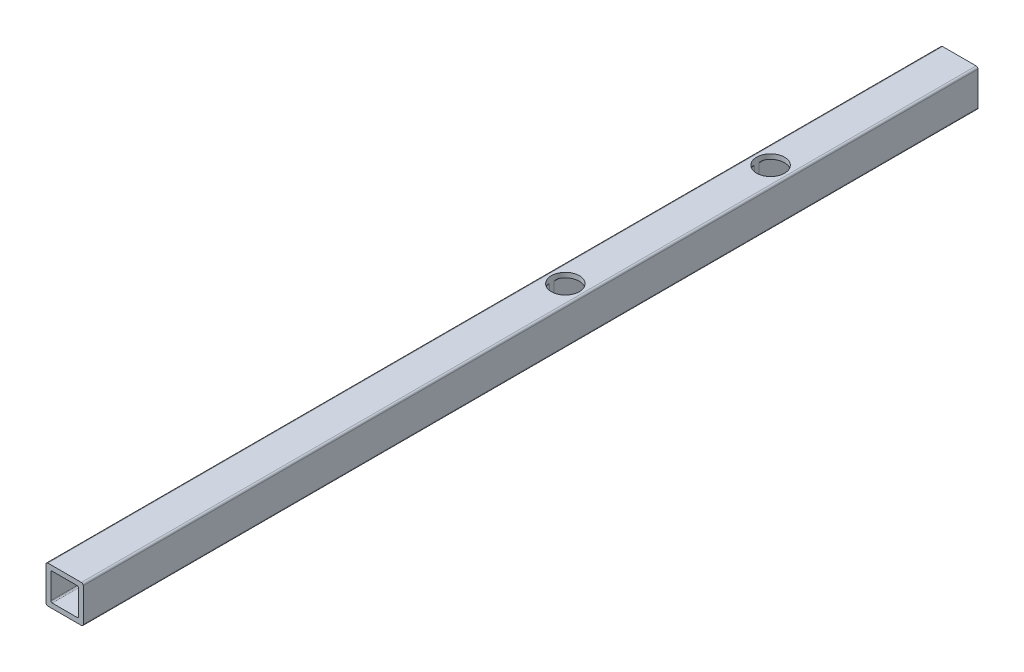
SolidWorks part; units mm, degrees
ref_plane "Front" through (0, 0, 0) normal (0, 0, 1) x (1, 0, 0)
ref_plane "Top" through (0, 0, 0) normal (0, 1, 0) x (1, 0, 0)
ref_plane "Right" through (0, 0, 0) normal (1, 0, 0) x (0, 0, -1)
sketch "Sketch1" plane through (0, 0, 0) normal (0, 0, 1) x (1, 0, 0)
  line L0 (-4.699, 0) -> (-6.35, 0) construction
  line L1 (5.715, -6.35) -> (-5.715, -6.35)
  line L2 (6.35, -5.715) -> (6.35, 5.715)
  line L3 (5.715, 6.35) -> (-5.715, 6.35)
  line L4 (-6.35, -5.715) -> (-6.35, 5.715)
  line L5 (6.35, -6.35) -> (-6.35, 6.35) construction
  line L6 (6.35, 6.35) -> (-6.35, -6.35) construction
  line L7 (4.2291, 4.699) -> (-4.2291, 4.699)
  line L8 (4.699, 4.2291) -> (4.699, -4.2291)
  line L9 (4.2291, -4.699) -> (-4.2291, -4.699)
  line L10 (-4.699, 4.2291) -> (-4.699, -4.2291)
  line L11 (4.699, 4.699) -> (-4.699, -4.699) construction
  line L12 (4.699, -4.699) -> (-4.699, 4.699) construction
  line L13 (0, -4.699) -> (0, -6.35) construction
  line L14 (4.699, -4.2291) -> (4.699, -6.35) construction
  line L15 (4.699, 0) -> (6.35, 0) construction
  line L16 (4.699, -6.35) -> (6.35, -6.35) construction
  arc A0 (-4.2291, -4.699) -> (-4.699, -4.2291) centre (-4.2291, -4.2291) cw
  arc A1 (4.699, -4.2291) -> (4.2291, -4.699) centre (4.2291, -4.2291) cw
  arc A2 (4.2291, 4.699) -> (4.699, 4.2291) centre (4.2291, 4.2291) cw
  arc A3 (-4.2291, 4.699) -> (-4.699, 4.2291) centre (-4.2291, 4.2291) ccw
  arc A4 (5.715, -6.35) -> (6.35, -5.715) centre (5.715, -5.715) ccw
  arc A5 (6.35, 5.715) -> (5.715, 6.35) centre (5.715, 5.715) ccw
  arc A6 (-5.715, 6.35) -> (-6.35, 5.715) centre (-5.715, 5.715) ccw
  arc A7 (-5.715, -6.35) -> (-6.35, -5.715) centre (-5.715, -5.715) cw
  point P0 (0, 0)
  point P6 (0, 0)
  dimension "D2" = 0.4699
  dimension "D3" = 0.635
  dimension "Outside Width" = 12.7
  dimension "Ouside Height" = 12.7
  dimension "Wall Thickness" = 1.651
sketch "Sketch2" plane through (0, 0, 0) normal (1, 0, 0) x (0, 0, -1)
  line L0 (-152.4, 0) -> (152.4, 0) construction
  dimension "Length" = 304.8
ref_plane "Plane1" through (6.35, 0, 0) normal (1, 0, 0) x (0, 0, -1)
sketch "Sketch5" plane through (6.35, 0, 0) normal (1, 0, 0) x (0, 0, -1)
  line L0 (-152.4, 6.35) -> (-152.4, -6.35) construction
  line L1 (152.4, 6.35) -> (152.4, -6.35) construction
sketch "Sketch4" plane through (0, 0, 0) normal (0, 0, 1) x (1, 0, 0)
  line L0 (6.35, -5.715) -> (6.35, 5.715) construction
  line L1 (5.715, 6.35) -> (-5.715, 6.35) construction
  line L2 (-6.35, -5.715) -> (-6.35, 5.715) construction
  line L3 (5.715, -6.35) -> (-5.715, -6.35) construction
  line L4 (4.699, 4.2291) -> (4.699, -4.2291) construction
  line L5 (4.2291, -4.699) -> (-4.2291, -4.699) construction
  line L6 (-4.699, 4.2291) -> (-4.699, -4.2291) construction
  line L7 (4.2291, 4.699) -> (-4.2291, 4.699) construction
  line L8 (6.35, -5.715) -> (6.35, 5.715)
  line L9 (5.715, 6.35) -> (-5.715, 6.35)
  line L10 (-6.35, -5.715) -> (-6.35, 5.715)
  line L11 (5.715, -6.35) -> (-5.715, -6.35)
  line L12 (4.699, 4.2291) -> (4.699, -4.2291)
  line L13 (4.2291, -4.699) -> (-4.2291, -4.699)
  line L14 (-4.699, 4.2291) -> (-4.699, -4.2291)
  line L15 (4.2291, 4.699) -> (-4.2291, 4.699)
  arc A0 (6.35, 5.715) -> (5.715, 6.35) centre (5.715, 5.715) ccw construction
  arc A1 (-5.715, 6.35) -> (-6.35, 5.715) centre (-5.715, 5.715) ccw construction
  arc A2 (-6.35, -5.715) -> (-5.715, -6.35) centre (-5.715, -5.715) ccw construction
  arc A3 (5.715, -6.35) -> (6.35, -5.715) centre (5.715, -5.715) ccw construction
  arc A4 (4.2291, -4.699) -> (4.699, -4.2291) centre (4.2291, -4.2291) ccw construction
  arc A5 (-4.699, -4.2291) -> (-4.2291, -4.699) centre (-4.2291, -4.2291) ccw construction
  arc A6 (-4.2291, 4.699) -> (-4.699, 4.2291) centre (-4.2291, 4.2291) ccw construction
  arc A7 (4.699, 4.2291) -> (4.2291, 4.699) centre (4.2291, 4.2291) ccw construction
  arc A8 (6.35, 5.715) -> (5.715, 6.35) centre (5.715, 5.715) ccw
  arc A9 (-5.715, 6.35) -> (-6.35, 5.715) centre (-5.715, 5.715) ccw
  arc A10 (-6.35, -5.715) -> (-5.715, -6.35) centre (-5.715, -5.715) ccw
  arc A11 (5.715, -6.35) -> (6.35, -5.715) centre (5.715, -5.715) ccw
  arc A12 (4.2291, -4.699) -> (4.699, -4.2291) centre (4.2291, -4.2291) ccw
  arc A13 (-4.699, -4.2291) -> (-4.2291, -4.699) centre (-4.2291, -4.2291) ccw
  arc A14 (-4.2291, 4.699) -> (-4.699, 4.2291) centre (-4.2291, 4.2291) ccw
  arc A15 (4.699, 4.2291) -> (4.2291, 4.699) centre (4.2291, 4.2291) ccw
extrude "Boss-Extrude1" add sketch "Sketch4" along normal up to vertex (152.4 mm away) and the other way up to vertex (152.4 mm away) up to point (0, 0, 152.4) other way up to point (0, 0, -152.4)
hole_wizard "3/8 (0.375) Diameter Hole1" positions "Sketch6" profile "Sketch7" hole size "3/8" standard "ANSI Inch" end condition through all
sketch "Sketch6" plane through (0, 6.35, 0) normal (0, 1, 0) x (1, 0, 0)
  point P0 (0, 88.0887)
  point P4 (-1.363, 88.1405)
  point P5 (0, 88.0887)
sketch "Sketch7" plane through (0, 6.35, -88.0887) normal (1, 0, 0) x (0, 0, 1)
  line L0 (0, 0) -> (0, 12.7)
  line L1 (0, 12.7) -> (4.7625, 12.7)
  line L2 (4.7625, 12.7) -> (4.7625, 0)
  line L5 (4.7625, 0) -> (0, 0)
  line L11 (0, -6.35) -> (0, 107.95) construction
  dimension "Thru Hole Dia." = 9.525
  dimension "Thru Hole Depth" = 12.7
hole_wizard "3/8 (0.375) Diameter Hole2" positions "Sketch8" profile "Sketch9" hole size "3/8" standard "ANSI Inch" end condition through all
sketch "Sketch8" plane through (0, 6.35, 0) normal (0, 1, 0) x (1, 0, 0)
  point P0 (0, 18.1666)
sketch "Sketch9" plane through (0, 6.35, -18.1666) normal (1, 0, 0) x (0, 0, 1)
  line L0 (0, 0) -> (0, 12.7)
  line L1 (0, 12.7) -> (4.7625, 12.7)
  line L2 (4.7625, 12.7) -> (4.7625, 0)
  line L5 (4.7625, 0) -> (0, 0)
  line L11 (0, -6.35) -> (0, 107.95) construction
  dimension "Thru Hole Dia." = 9.525
  dimension "Thru Hole Depth" = 12.7
equation "\"D3@Sketch1\"=\"Outside Width@Sketch1\"*.05"
equation "\"D2@Sketch1\"=\"D1@Sketch1\"*.05"
